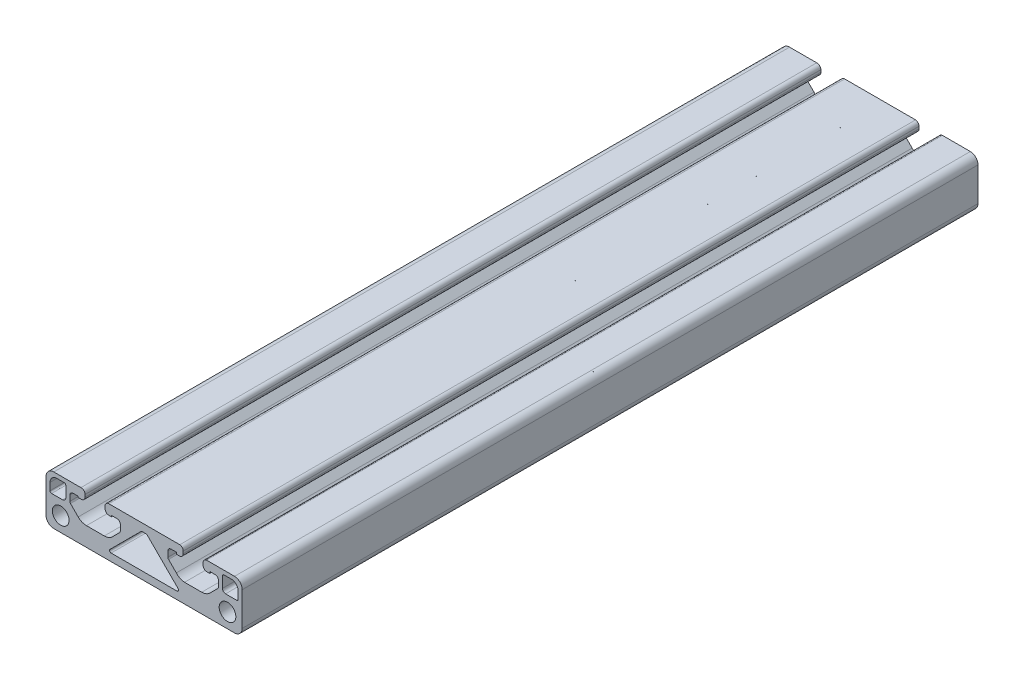
SolidWorks part; units mm, degrees
material "6105-T5 Aluminum"
ref_plane "Front Plane" through (0, 0, 0) normal (0, 0, 1) x (1, 0, 0)
ref_plane "Top Plane" through (0, 0, 0) normal (0, 1, 0) x (1, 0, 0)
ref_plane "Right Plane" through (0, 0, 0) normal (1, 0, 0) x (0, 0, -1)
sketch "Sketch1" plane through (0, 0, 0) normal (0, 0, 1) x (1, 0, 0)
  line L0 (0, -10) -> (0, 10) construction
  line L1 (-40, 0) -> (40, 0) construction
  line L2 (-20, -2.3) -> (-20, 13.0699) construction
  line L3 (20, -2.3) -> (20, 13.0699) construction
  line L4 (34.0048, -14.2627) -> (34.0048, 0) construction
  line L5 (-34.0048, -15.6676) -> (-34.0048, 0) construction
  line L6 (-36.8282, 10) -> (-25.7617, 10)
  line L7 (-14.3654, 10) -> (-7.0441, 10)
  line L8 (-7.0441, 10) -> (14.5525, 10)
  line L9 (-34.0048, -4) -> (34.0048, -4) construction
  line L11 (25.4475, 10) -> (33.0758, 10)
  line L12 (-26.8986, 5.9365) -> (-25.7617, 5.9365)
  line L13 (-14.3654, 5.9365) -> (-13.2285, 5.9365)
  line L14 (13.2285, 6.6606) -> (13.2285, 5.9365)
  line L15 (13.2285, 5.9365) -> (14.3654, 5.9365)
  line L16 (10.9848, 6.6606) -> (13.2285, 6.6606)
  line L17 (-23.5072, -2.3) -> (-16.2347, -2.3)
  line L19 (-29.0152, 6.4054) -> (-26.8986, 6.4054)
  line L21 (-36.8282, -10) -> (36.8254, -10)
  line L52 (-38.35, 2.5953) -> (-38.35, 5.5571)
  line L53 (-33.2048, 1.9604) -> (-37.7151, 1.9604)
  line L54 (-31.935, 7.7151) -> (-31.935, 3.2302)
  line L55 (-35.4935, 8.35) -> (-32.5699, 8.35)
  line L57 (13.4502, -6.9544) -> (-13.4502, -6.9544)
  line L58 (0, 6.9552) -> (-0.8088, 6.9553)
  line L59 (-13.8991, -5.8705) -> (-1.2578, 6.7693)
  line L60 (40, 6.8282) -> (40, -6.8282)
  line L61 (33.0758, 10) -> (36.8854, 10)
  line L63 (24.06, 7.5111) -> (24.06, 8.4254)
  line L64 (26.7715, 5.9365) -> (25.6346, 5.9365)
  line L65 (26.7715, 6.6606) -> (26.7715, 5.9365)
  line L66 (29.0152, 6.6606) -> (26.7715, 6.6606)
  line L67 (30.285, 3.1342) -> (30.285, 5.3908)
  line L68 (26.8655, -0.9089) -> (30.0247, 2.2504)
  line L69 (16.4928, -2.3) -> (23.5072, -2.3)
  line L70 (9.9753, 2.5057) -> (13.1345, -0.6536)
  line L71 (9.715, 5.3908) -> (9.715, 3.1342)
  line L75 (15.94, 8.4254) -> (15.94, 7.5111)
  line L79 (13.8991, -5.8705) -> (1.2578, 6.7693)
  line L80 (0, 6.9552) -> (0.8088, 6.9553)
  line L81 (35.5549, 8.35) -> (32.564, 8.35)
  line L82 (31.935, 7.7219) -> (31.935, 3.2459)
  line L83 (33.2048, 1.976) -> (37.6808, 1.976)
  line L84 (38.35, 2.5356) -> (38.35, 5.4968)
  line L88 (-15.94, 8.4254) -> (-15.94, 7.5111)
  line L90 (-13.2285, 5.9365) -> (-13.2285, 6.4054)
  line L91 (-13.2285, 6.4054) -> (-10.9848, 6.4054)
  line L92 (-9.715, 5.1355) -> (-9.715, 2.6208)
  line L93 (-9.9753, 1.9923) -> (-12.8764, -0.9089)
  line L95 (-26.8655, -0.9089) -> (-30.0247, 2.2504)
  line L96 (-30.285, 2.879) -> (-30.285, 5.1355)
  line L98 (-26.8986, 6.4054) -> (-26.8986, 5.9365)
  line L100 (-24.06, 7.506) -> (-24.06, 8.4203)
  line L103 (-40, 6.8282) -> (-40, -6.8282)
  arc A38 (36.8854, 10) -> (40, 6.8282) centre (36.8254, 6.826) cw
  circle A39 centre (-34.0048, -4) radius 3.4
  arc A40 (-38.35, 2.5953) -> (-37.7151, 1.9604) centre (-37.7151, 2.5953) ccw
  arc A41 (-33.2048, 1.9604) -> (-31.935, 3.2302) centre (-33.2048, 3.2302) ccw
  arc A42 (-35.4935, 8.35) -> (-38.35, 5.5571) centre (-35.5563, 5.5571) ccw
  arc A43 (-31.935, 7.7151) -> (-32.5699, 8.35) centre (-32.5699, 7.7151) ccw
  arc A44 (-13.8991, -5.8705) -> (-13.4502, -6.9544) centre (-13.4502, -6.3195) ccw
  arc A45 (-0.8088, 6.9553) -> (-1.2578, 6.7693) centre (-0.8088, 6.3203) ccw
  arc A46 (24.06, 8.4254) -> (25.4475, 10) centre (25.6346, 8.4365) cw
  arc A47 (25.6346, 5.9365) -> (24.06, 7.5111) centre (25.6346, 7.5111) cw
  arc A48 (29.0152, 6.6606) -> (30.285, 5.3908) centre (29.0152, 5.3908) cw
  arc A49 (30.285, 3.1342) -> (30.0247, 2.2504) centre (29.4256, 2.9071) cw
  arc A50 (26.8655, -0.9089) -> (23.5072, -2.3) centre (23.5072, 2.4492) cw
  arc A51 (16.4928, -2.3) -> (13.1345, -0.6536) centre (16.7353, 2.443) cw
  arc A52 (9.9753, 2.5057) -> (9.715, 3.1342) centre (10.6039, 3.1342) cw
  arc A53 (9.715, 5.3908) -> (10.9848, 6.6606) centre (10.9848, 5.3908) cw
  arc A54 (15.94, 7.5111) -> (14.3654, 5.9365) centre (14.3654, 7.5111) cw
  arc A55 (14.5525, 10) -> (15.94, 8.4254) centre (14.3654, 8.4365) cw
  arc A56 (40, -6.8282) -> (36.8254, -10) centre (36.8254, -6.8254) cw
  arc A57 (0.8088, 6.9553) -> (1.2578, 6.7693) centre (0.8088, 6.3203) cw
  arc A58 (13.8991, -5.8705) -> (13.4502, -6.9544) centre (13.4502, -6.3195) cw
  arc A59 (31.935, 7.7219) -> (32.564, 8.35) centre (32.5699, 7.7151) cw
  arc A60 (35.5549, 8.35) -> (38.35, 5.4968) centre (35.557, 5.5563) cw
  arc A61 (33.2048, 1.976) -> (31.935, 3.2459) centre (33.2048, 3.2459) cw
  arc A62 (38.35, 2.5356) -> (37.6808, 1.976) centre (37.7194, 2.6098) cw
  circle A63 centre (34.0048, -4) radius 3.4
  arc A64 (-40, -6.8282) -> (-36.8282, -10) centre (-36.8282, -6.8282) ccw
  arc A65 (-14.3654, 10) -> (-15.94, 8.4254) centre (-14.3654, 8.4254) ccw
  arc A66 (-15.94, 7.5111) -> (-14.3654, 5.9365) centre (-14.3654, 7.5111) ccw
  arc A67 (-9.715, 5.1355) -> (-10.9848, 6.4054) centre (-10.9848, 5.1355) ccw
  arc A68 (-9.9753, 1.9923) -> (-9.715, 2.6208) centre (-10.6039, 2.6208) ccw
  arc A69 (-16.2347, -2.3) -> (-12.8764, -0.9089) centre (-16.2347, 2.4492) ccw
  arc A70 (-26.8655, -0.9089) -> (-23.5072, -2.3) centre (-23.5072, 2.4492) ccw
  arc A71 (-30.285, 2.879) -> (-30.0247, 2.2504) centre (-29.3961, 2.879) ccw
  arc A72 (-29.0152, 6.4054) -> (-30.285, 5.1355) centre (-29.0152, 5.1355) ccw
  arc A73 (-25.7617, 5.9365) -> (-24.06, 7.506) centre (-25.6346, 7.506) ccw
  arc A74 (-24.06, 8.4203) -> (-25.7617, 10) centre (-25.6441, 8.4203) ccw
  arc A75 (-36.8282, 10) -> (-40, 6.8282) centre (-36.8282, 6.8282) ccw
  dimension "D4" = 6.8
  dimension "D1" = 20
  dimension "D2" = 80
  dimension "D3" = 40
  dimension "D5" = 6
  dimension "D6" = 8.12
  dimension "D7" = 4.0635
  dimension "D8" = 20.57
  dimension "D9" = 12.3
  dimension "D10" = 20
extrude "Extrude1" add sketch "Sketch1" against normal blind 300
